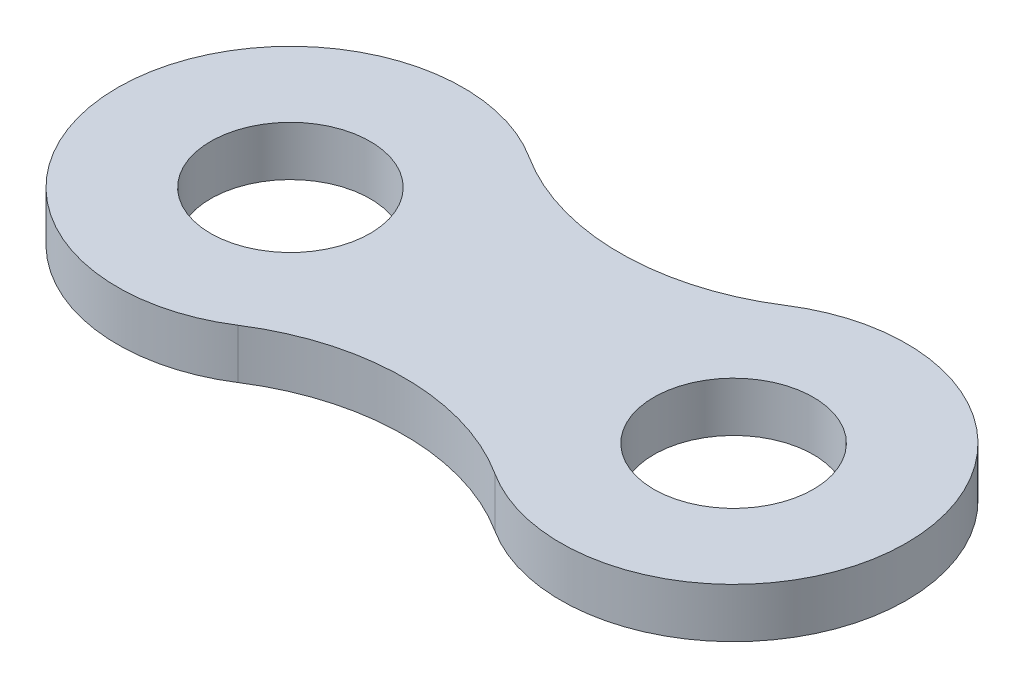
SolidWorks part; units mm, degrees
material "AISI 1020 Steel, Cold Rolled"
ref_plane "Front Plane" through (0, 0, 0) normal (0, 0, 1) x (1, 0, 0)
ref_plane "Top Plane" through (0, 0, 0) normal (0, 1, 0) x (1, 0, 0)
ref_plane "Right Plane" through (0, 0, 0) normal (1, 0, 0) x (0, 0, -1)
sketch "Sketch1" plane through (0, 0, 0) normal (0, 1, 0) x (1, 0, 0)
  line L0 (-10.4692, 0) -> (13.5503, 0) construction
  circle A0 centre (0, 0) radius 1.143
  circle A1 centre (6.35, 0) radius 1.143
  arc A2 (1.3365, 2.0849) -> (1.3365, -2.0849) centre (0, 0) ccw
  arc A3 (5.0135, -2.0849) -> (5.0135, 2.0849) centre (6.35, 0) ccw
  arc A4 (1.3365, 2.0849) -> (5.0135, 2.0849) centre (3.175, 4.953) ccw
  arc A5 (1.3365, -2.0849) -> (5.0135, -2.0849) centre (3.175, -4.953) cw
  dimension "D1" = 2.286
  dimension "D3" = 4.953
  dimension "D4" = 4.953
  dimension "D2" = 6.35
extrude "Boss-Extrude1" add sketch "Sketch1" along normal blind 0.7112
